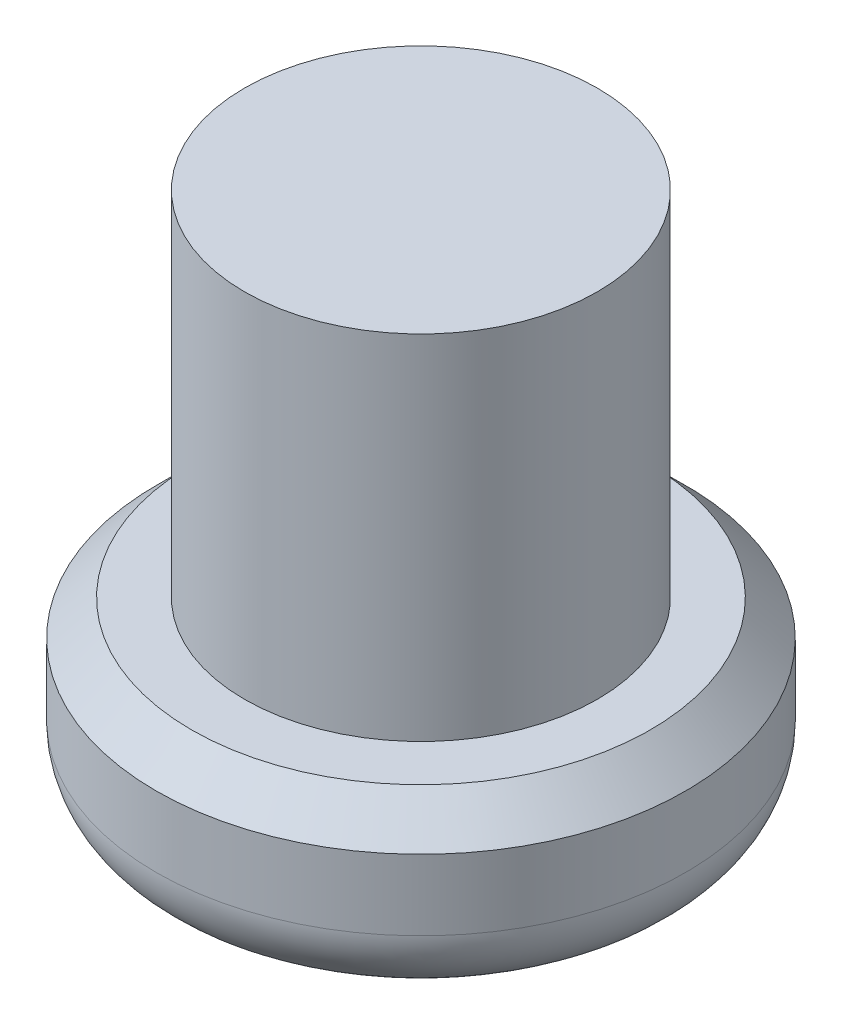
SolidWorks part; units mm, degrees
ref_plane "Front Plane" through (0, 0, 0) normal (0, 0, 1) x (1, 0, 0)
ref_plane "Top Plane" through (0, 0, 0) normal (0, 1, 0) x (1, 0, 0)
ref_plane "Right Plane" through (0, 0, 0) normal (1, 0, 0) x (0, 0, -1)
sketch "Sketch1" plane through (0, 0, 0) normal (0, 1, 0) x (1, 0, 0)
  circle A0 centre (0, 0) radius 7.5
  dimension "D1" = 15
extrude "Boss-Extrude1" add sketch "Sketch1" along normal blind 5
chamfer "Chamfer1" [suppressed] distance 1 angle 45
fillet "Fillet1" radius 2 1 edges at (0, 0, 7.5)
sketch "Sketch2" plane through (0, 5, 0) normal (0, 1, 0) x (1, 0, 0)
  circle A0 centre (0, 0) radius 5
  dimension "D1" = 10
extrude "Boss-Extrude2" add sketch "Sketch2" along normal blind 10
chamfer "Chamfer2" distance 1 angle 45 1 edges at (0, 5, 7.5)
